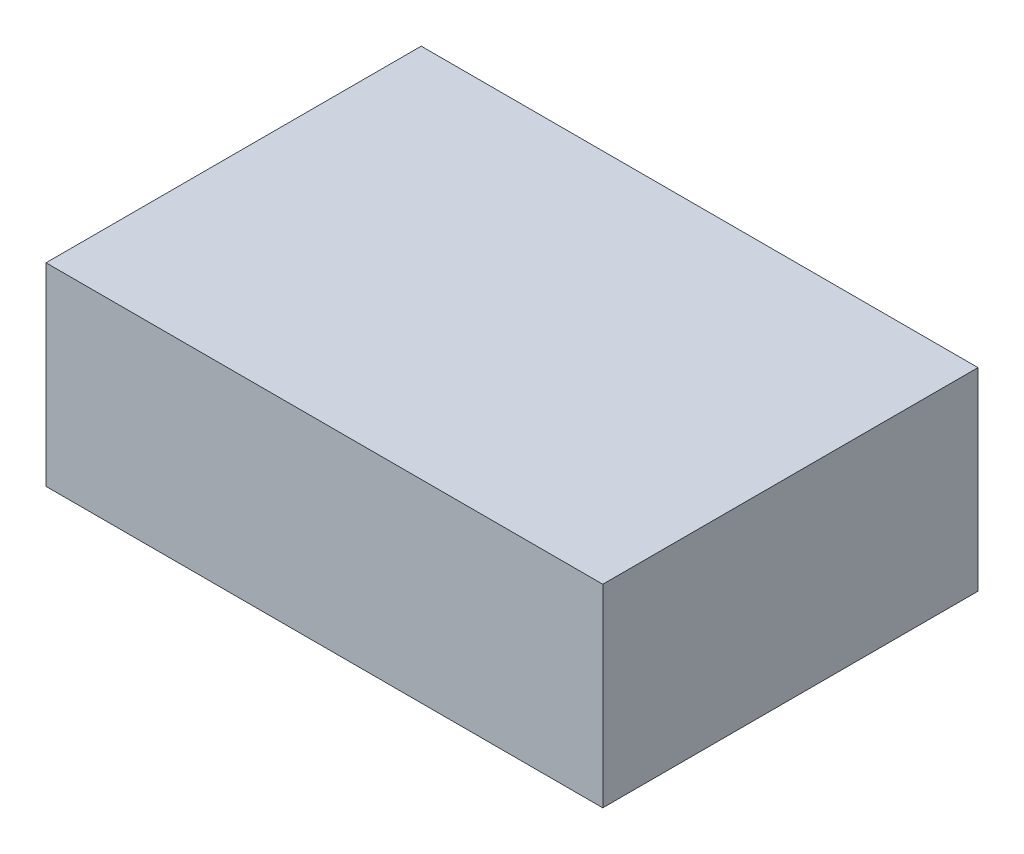
SolidWorks part; units mm, degrees
ref_plane "Front Plane" through (0, 0, 0) normal (0, 0, 1) x (1, 0, 0)
ref_plane "Top Plane" through (0, 0, 0) normal (0, 1, 0) x (1, 0, 0)
ref_plane "Right Plane" through (0, 0, 0) normal (1, 0, 0) x (0, 0, -1)
sketch "Sketch1" plane through (0, 0, 0) normal (0, 1, 0) x (1, 0, 0)
  line L1 (-23, 15.5) -> (23, 15.5)
  line L2 (-23, 15.5) -> (-23, -15.5)
  line L3 (-23, -15.5) -> (23, -15.5)
  line L4 (23, 15.5) -> (23, -15.5)
  line L5 (-23, 15.5) -> (23, -15.5) construction
  line L6 (-23, -15.5) -> (23, 15.5) construction
  point P0 (0, 0)
  dimension "D1" = 46
  dimension "D2" = 31
extrude "Boss-Extrude1" add sketch "Sketch1" along normal blind 16
